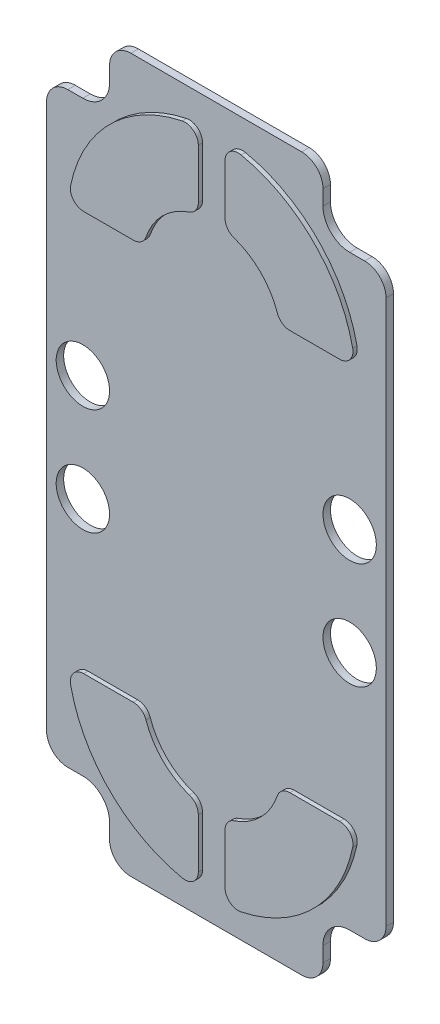
SolidWorks part; units mm, degrees
ref_plane "Front Plane" through (0, 0, 0) normal (0, 0, 1) x (1, 0, 0)
ref_plane "Top Plane" through (0, 0, 0) normal (0, 1, 0) x (1, 0, 0)
ref_plane "Right Plane" through (0, 0, 0) normal (1, 0, 0) x (0, 0, -1)
sketch "Sketch1" plane through (0, 0, 0) normal (0, 0, 1) x (1, 0, 0)
  line L16 (20, 60) -> (20, 62.81)
  line L18 (31.81, 51) -> (31.81, -51)
  line L20 (-31.81, 51) -> (-31.81, -51)
  line L23 (-16, 66.81) -> (16, 66.81)
  line L25 (25, 55) -> (27.81, 55)
  line L26 (-20, 60) -> (-20, 62.81)
  line L27 (-25, 55) -> (-27.81, 55)
  line L29 (-25, -55) -> (-27.81, -55)
  line L30 (-20, -60) -> (-20, -62.81)
  line L31 (25, -55) -> (27.81, -55)
  line L32 (-16, -66.81) -> (16, -66.81)
  line L33 (20, -60) -> (20, -62.81)
  arc A0 (-25, 55) -> (-20, 60) centre (-25, 60) ccw
  arc A1 (20, 60) -> (25, 55) centre (25, 60) ccw
  circle A2 centre (-25, 10) radius 5
  circle A3 centre (25, 10) radius 5
  circle A28 centre (-25, -10) radius 5
  circle A29 centre (25, -10) radius 5
  arc A60 (27.81, 55) -> (31.81, 51) centre (27.81, 51) cw
  arc A61 (20, 62.81) -> (16, 66.81) centre (16, 62.81) ccw
  arc A62 (-27.81, 55) -> (-31.81, 51) centre (-27.81, 51) ccw
  arc A63 (-20, 62.81) -> (-16, 66.81) centre (-16, 62.81) cw
  arc A64 (-20, -62.81) -> (-16, -66.81) centre (-16, -62.81) ccw
  arc A65 (-27.81, -55) -> (-31.81, -51) centre (-27.81, -51) cw
  arc A66 (20, -62.81) -> (16, -66.81) centre (16, -62.81) cw
  arc A67 (27.81, -55) -> (31.81, -51) centre (27.81, -51) ccw
  arc A68 (20, -60) -> (25, -55) centre (25, -60) cw
  arc A69 (-25, -55) -> (-20, -60) centre (-25, -60) cw
extrude "Boss-Extrude1" add sketch "Sketch1" along normal blind 1.4
sketch "Sketch2" plane through (0, 0, 1.4) normal (0, 0, 1) x (1, 0, 0)
  line L1 (-24.049, 37.5) -> (-14.736, 37.5)
  line L2 (-2.5646, 49.6714) -> (-2.5646, 58.9844)
  line L3 (23.9198, 37.5) -> (14.6068, 37.5)
  line L4 (2.4354, 49.6714) -> (2.4354, 58.9844)
  line L5 (-24.049, -37.5) -> (-14.736, -37.5)
  line L6 (-2.5646, -49.6714) -> (-2.5646, -58.9844)
  line L7 (2.4354, -49.6714) -> (2.4354, -58.9844)
  line L8 (23.9198, -37.5) -> (14.6068, -37.5)
  arc A0 (-26.4963, 40.5102) -> (-24.049, 37.5) centre (-24.049, 40) ccw
  arc A1 (-14.736, 37.5) -> (-12.3696, 39.1935) centre (-14.736, 40) ccw
  arc A2 (-2.5646, 58.9844) -> (-5.5748, 61.4318) centre (-5.0646, 58.9844) ccw
  arc A3 (-4.2581, 47.305) -> (-2.5646, 49.6714) centre (-5.0646, 49.6714) ccw
  arc A4 (-5.5748, 61.4318) -> (-26.4963, 40.5102) centre (-0.0646, 35) ccw
  arc A5 (-4.2581, 47.305) -> (-12.3696, 39.1935) centre (-0.0646, 35) ccw
  arc A6 (26.3672, 40.5102) -> (23.9198, 37.5) centre (23.9198, 40) cw
  arc A7 (5.4456, 61.4318) -> (26.3672, 40.5102) centre (-0.0646, 35) cw
  arc A8 (2.4354, 58.9844) -> (5.4456, 61.4318) centre (4.9354, 58.9844) cw
  arc A9 (4.129, 47.305) -> (2.4354, 49.6714) centre (4.9354, 49.6714) cw
  arc A10 (4.129, 47.305) -> (12.2405, 39.1935) centre (-0.0646, 35) cw
  arc A11 (14.6068, 37.5) -> (12.2405, 39.1935) centre (14.6068, 40) cw
  arc A12 (-26.4963, -40.5102) -> (-24.049, -37.5) centre (-24.049, -40) cw
  arc A13 (-5.5748, -61.4318) -> (-26.4963, -40.5102) centre (-0.0646, -35) cw
  arc A14 (-2.5646, -58.9844) -> (-5.5748, -61.4318) centre (-5.0646, -58.9844) cw
  arc A15 (-4.2581, -47.305) -> (-2.5646, -49.6714) centre (-5.0646, -49.6714) cw
  arc A16 (-4.2581, -47.305) -> (-12.3696, -39.1935) centre (-0.0646, -35) cw
  arc A17 (-14.736, -37.5) -> (-12.3696, -39.1935) centre (-14.736, -40) cw
  arc A18 (26.3672, -40.5102) -> (23.9198, -37.5) centre (23.9198, -40) ccw
  arc A19 (5.4456, -61.4318) -> (26.3672, -40.5102) centre (-0.0646, -35) ccw
  arc A20 (2.4354, -58.9844) -> (5.4456, -61.4318) centre (4.9354, -58.9844) ccw
  arc A21 (4.129, -47.305) -> (2.4354, -49.6714) centre (4.9354, -49.6714) ccw
  arc A22 (4.129, -47.305) -> (12.2405, -39.1935) centre (-0.0646, -35) ccw
  arc A23 (14.6068, -37.5) -> (12.2405, -39.1935) centre (14.6068, -40) ccw
extrude "Boss-Extrude2" add sketch "Sketch2" along normal blind 0.8
